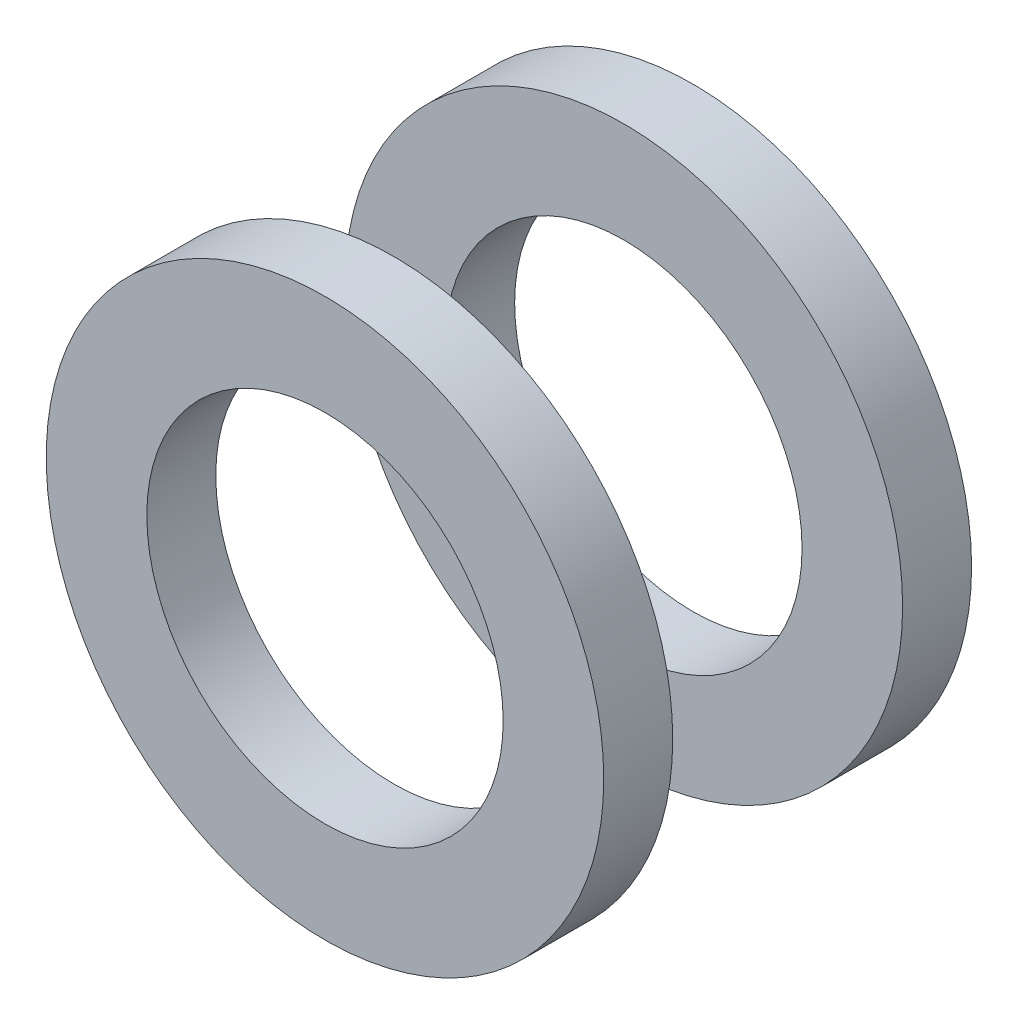
SolidWorks part; units mm, degrees
ref_plane "Спереди" through (0, 0, 0) normal (0, 0, 1) x (1, 0, 0)
ref_plane "Сверху" through (0, 0, 0) normal (0, 1, 0) x (1, 0, 0)
ref_plane "Справа" through (0, 0, 0) normal (1, 0, 0) x (0, 0, -1)
sketch "Эскиз1" plane through (0, 0, 0) normal (0, 0, 1) x (1, 0, 0)
  circle A0 centre (0, 0) radius 48.5
  circle A1 centre (0, 0) radius 31
extrude "Rear_endturn" add sketch "Эскиз1" along normal blind 12 from offset 32 separate body
sketch "Эскиз2" plane through (0, 0, 0) normal (0, 0, 1) x (1, 0, 0)
  circle A0 centre (0, 0) radius 48.5
  circle A1 centre (0, 0) radius 31
extrude "Front_endturn" add sketch "Эскиз2" along normal blind 12 from offset 20 separate body
